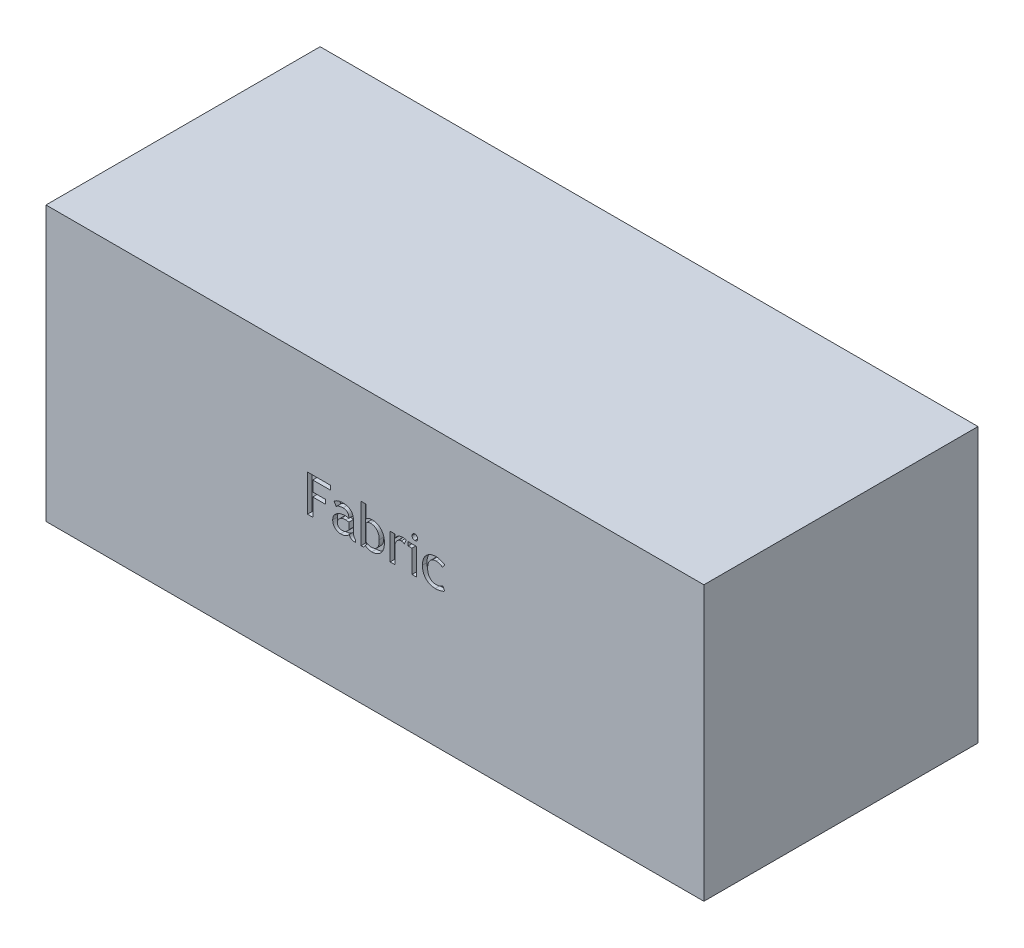
SolidWorks part; units mm, degrees
ref_plane "Front Plane" through (0, 0, 0) normal (0, 0, 1) x (1, 0, 0)
ref_plane "Top Plane" through (0, 0, 0) normal (0, 1, 0) x (1, 0, 0)
ref_plane "Right Plane" through (0, 0, 0) normal (1, 0, 0) x (0, 0, -1)
sketch "Sketch1" plane through (0, 0, 0) normal (0, 1, 0) x (1, 0, 0)
  line L1 (-914.4, -381) -> (914.4, -381)
  line L2 (-914.4, -381) -> (-914.4, 381)
  line L3 (-914.4, 381) -> (914.4, 381)
  line L4 (914.4, -381) -> (914.4, 381)
  line L5 (-914.4, -381) -> (914.4, 381) construction
  line L6 (-914.4, 381) -> (914.4, -381) construction
  point P0 (0, 0)
  dimension "D1" = 1828.8
  dimension "D2" = 762
extrude "Boss-Extrude1" add sketch "Sketch1" along normal blind 762
sketch "Sketch2" plane through (0, 0, 381) normal (0, 0, 1) x (1, 0, 0)
  line L0 (-914.4, 381) -> (914.4, 381) construction
  line L1 (-914.4, 762) -> (-914.4, 0) construction
  line L2 (914.4, 762) -> (914.4, 0) construction
  text T0 "Fabric" font "Trebuchet MS" height 101.6
extrude "Cut-Extrude1" cut sketch "Sketch2" against normal blind 12.7
